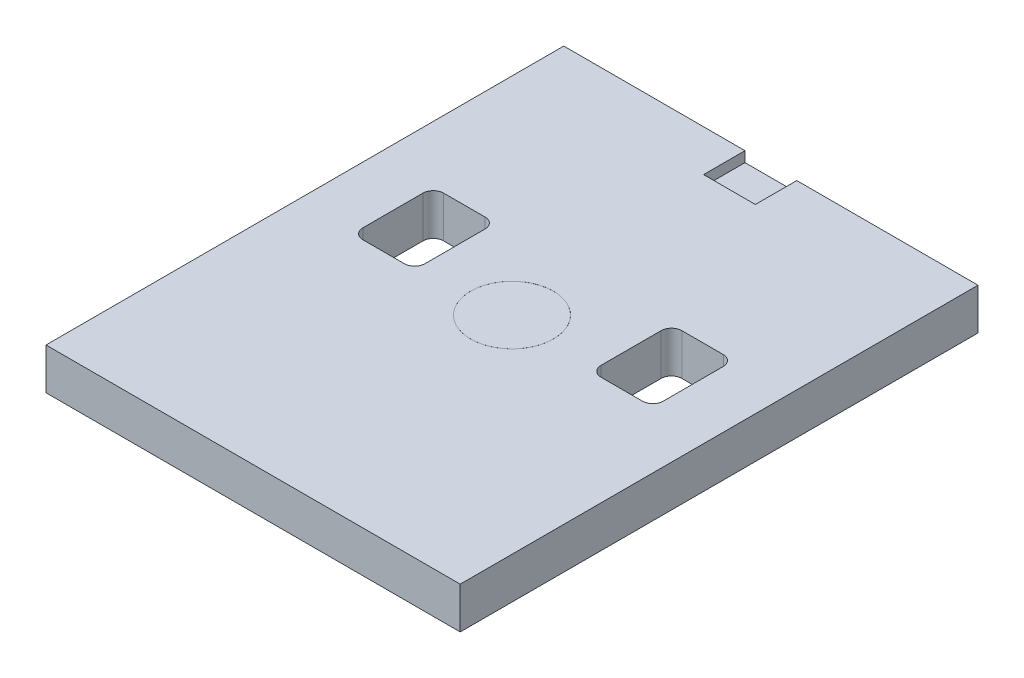
SolidWorks part; units mm, degrees
ref_plane "front" through (0, 0, 0) normal (0, 0, 1) x (1, 0, 0)
ref_plane "top" through (0, 0, 0) normal (0, 1, 0) x (1, 0, 0)
ref_plane "right" through (0, 0, 0) normal (1, 0, 0) x (0, 0, -1)
sketch "Sketch1" plane through (0, 0, 0) normal (0, 1, 0) x (1, 0, 0)
  line L1 (-165.1, 158.75) -> (-127, 158.75)
  line L2 (-165.1, 158.75) -> (-165.1, -158.75)
  line L3 (-165.1, -158.75) -> (165.1, -158.75)
  line L4 (165.1, 158.75) -> (165.1, -158.75)
  line L5 (60.325, 43.815) -> (85.725, 43.815)
  line L6 (53.975, 37.465) -> (53.975, 0.635)
  line L7 (60.325, -5.715) -> (85.725, -5.715)
  line L8 (92.075, 37.465) -> (92.075, 0.635)
  line L9 (0, -128.8632) -> (0, 117.3388) construction
  line L21 (-127, 158.75) -> (165.1, 158.75)
  line L22 (-127, 158.75) -> (-127, -158.75)
  line L23 (127, 158.75) -> (127, -158.75)
  circle A0 centre (0, 0) radius 25.4 construction
  arc A1 (85.725, -5.715) -> (92.075, 0.635) centre (85.725, 0.635) ccw
  arc A2 (85.725, 43.815) -> (92.075, 37.465) centre (85.725, 37.465) cw
  arc A3 (60.325, 43.815) -> (53.975, 37.465) centre (60.325, 37.465) ccw
  arc A4 (53.975, 0.635) -> (60.325, -5.715) centre (60.325, 0.635) ccw
  point P13 (92.075, -5.715)
  point P21 (0, -158.75)
  point P22 (165.1, 0)
  point P32 (92.075, 43.815)
  point P35 (53.975, 43.815)
  point P38 (53.975, -5.715)
  dimension "D5" = 50.8
  dimension "D8" = 6.35
  dimension "D1" = 317.5
  dimension "D2" = 330.2
  dimension "D3" = 153.035
  dimension "D4" = 38.1
  dimension "D6" = 49.53
  dimension "D7" = 53.975
  dimension "D12" = 38.1
  dimension "D13" = 38.1
sketch "Sketch2" plane through (0, 0, 0) normal (0, 1, 0) x (1, 0, 0)
  line L8 (127, 158.75) -> (127, -158.75) construction
  line L9 (-127, 158.75) -> (-127, -158.75) construction
  line L10 (127, 158.75) -> (127, -158.75)
  line L11 (-127, 158.75) -> (-127, -158.75)
  line L12 (-165.1, -158.75) -> (165.1, -158.75) construction
  line L18 (60.325, 43.815) -> (85.725, 43.815) construction
  line L19 (92.075, 37.465) -> (92.075, 0.635) construction
  line L20 (60.325, -5.715) -> (85.725, -5.715) construction
  line L21 (53.975, 37.465) -> (53.975, 0.635) construction
  line L22 (60.325, 43.815) -> (85.725, 43.815)
  line L23 (92.075, 37.465) -> (92.075, 0.635)
  line L24 (60.325, -5.715) -> (85.725, -5.715)
  line L25 (-127, 158.75) -> (165.1, 158.75) construction
  line L28 (-127, -158.75) -> (127, -158.75)
  line L29 (53.975, 37.465) -> (53.975, 0.635)
  line L32 (0, -102.1476) -> (0, 99.0046) construction
  line L33 (-127, 158.75) -> (127, 158.75)
  line L37 (0, -128.8632) -> (0, 117.3388) construction
  line L38 (-53.975, 37.465) -> (-53.975, 0.635)
  line L39 (-60.325, -5.715) -> (-85.725, -5.715)
  line L40 (-92.075, 37.465) -> (-92.075, 0.635)
  line L41 (-60.325, 43.815) -> (-85.725, 43.815)
  arc A0 (60.325, 43.815) -> (53.975, 37.465) centre (60.325, 37.465) ccw construction
  arc A1 (92.075, 37.465) -> (85.725, 43.815) centre (85.725, 37.465) ccw construction
  arc A2 (85.725, -5.715) -> (92.075, 0.635) centre (85.725, 0.635) ccw construction
  arc A3 (53.975, 0.635) -> (60.325, -5.715) centre (60.325, 0.635) ccw construction
  arc A4 (60.325, 43.815) -> (53.975, 37.465) centre (60.325, 37.465) ccw
  arc A5 (92.075, 37.465) -> (85.725, 43.815) centre (85.725, 37.465) ccw
  arc A6 (85.725, -5.715) -> (92.075, 0.635) centre (85.725, 0.635) ccw
  arc A7 (53.975, 0.635) -> (60.325, -5.715) centre (60.325, 0.635) ccw
  arc A8 (-53.975, 0.635) -> (-60.325, -5.715) centre (-60.325, 0.635) cw
  arc A9 (-85.725, -5.715) -> (-92.075, 0.635) centre (-85.725, 0.635) cw
  arc A10 (-92.075, 37.465) -> (-85.725, 43.815) centre (-85.725, 37.465) cw
  arc A11 (-60.325, 43.815) -> (-53.975, 37.465) centre (-60.325, 37.465) cw
extrude "Extrude1" add sketch "Sketch2" along normal blind 25.4
sketch "Sketch3" plane through (0, 0, 0) normal (0, 1, 0) x (1, 0, 0)
  circle A0 centre (0, 0) radius 25.4 construction
  circle A1 centre (0, 0) radius 25.4
  circle A2 centre (0, 0) radius 25.3746
  dimension "D1" = 0.0254
extrude "Cut-Extrude1" cut sketch "Sketch3" along normal through all
sketch "Sketch4" plane through (0, 25.4, 0) normal (0, 1, 0) x (1, 0, 0)
  line L0 (127, 158.75) -> (-127, 158.75) construction
  line L1 (-15.875, 133.35) -> (15.875, 133.35)
  line L2 (-15.875, 133.35) -> (-15.875, 197.9345)
  line L3 (-15.875, 197.9345) -> (15.875, 197.9345)
  line L4 (15.875, 133.35) -> (15.875, 197.9345)
  point P4 (0, 133.35)
  dimension "D1" = 25.4
  dimension "D2" = 31.75
extrude "Cut-Extrude2" cut sketch "Sketch4" against normal blind 6.35
